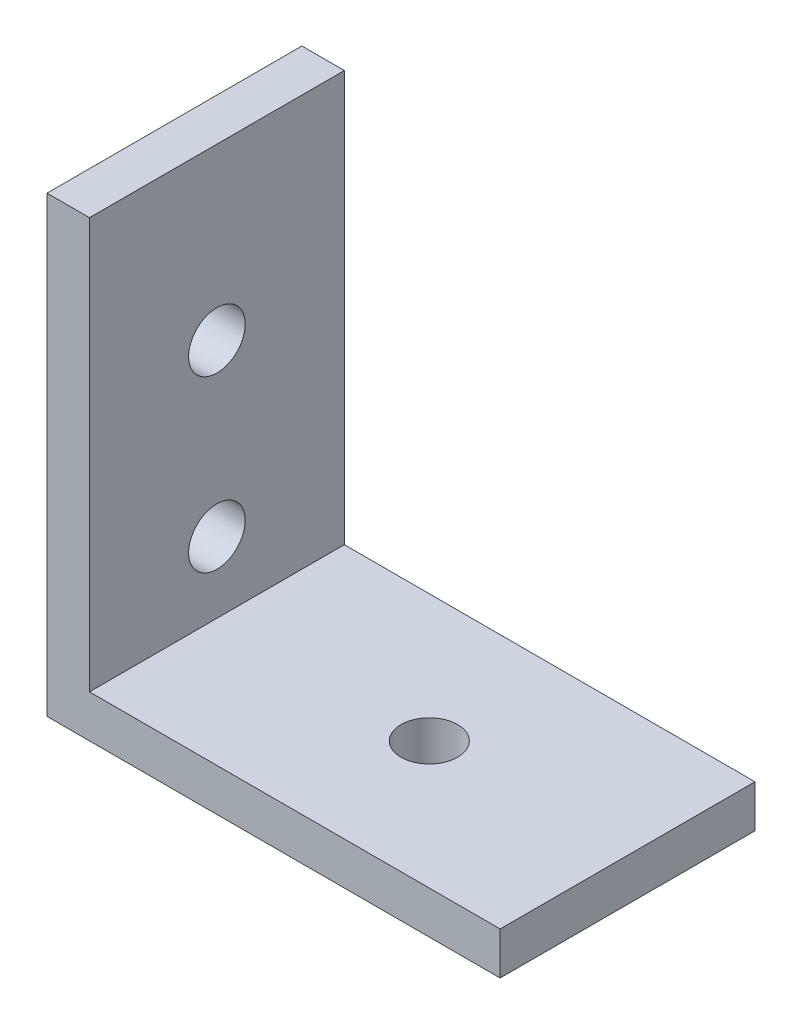
SolidWorks part; units mm, degrees
material "6063-O"
ref_plane "Front Plane" through (0, 0, 0) normal (0, 0, 1) x (1, 0, 0)
ref_plane "Top Plane" through (0, 0, 0) normal (0, 1, 0) x (1, 0, 0)
ref_plane "Right Plane" through (0, 0, 0) normal (1, 0, 0) x (0, 0, -1)
sketch "Sketch1" plane through (0, 0, 0) normal (0, 1, 0) x (1, 0, 0)
  line L1 (0, 0) -> (32, 0)
  line L2 (0, 0) -> (0, 18)
  line L3 (0, 18) -> (32, 18)
  line L4 (32, 0) -> (32, 18)
  dimension "D1" = 18
  dimension "D2" = 32
extrude "Boss-Extrude1" add sketch "Sketch1" along normal blind 3
sketch "Sketch2" plane through (0, 3, 0) normal (0, 1, 0) x (1, 0, 0)
  line L0 (32, 18) -> (0, 18) construction
  line L1 (0, 0) -> (3, 0)
  line L2 (0, 0) -> (0, 18)
  line L3 (0, 18) -> (3, 18)
  line L4 (3, 0) -> (3, 18)
  dimension "D1" = 3
extrude "Boss-Extrude2" add sketch "Sketch2" along normal blind 29
sketch "Sketch3" plane through (0, 3, 0) normal (0, 1, 0) x (1, 0, 0)
  line L1 (32, 0) -> (32, 18) construction
  line L2 (32, 18) -> (3, 18) construction
  circle A0 centre (18, 9) radius 2
  dimension "D1" = 14
  dimension "D3" = 4
  dimension "D2" = 9
extrude "Cut-Extrude1" cut sketch "Sketch3" against normal through all
sketch "Sketch4" plane through (3, 0, 0) normal (1, 0, 0) x (0, 0, -1)
  line L0 (0, 32) -> (0, 3) construction
  line L1 (0, 32) -> (18, 32) construction
  circle A0 centre (9, 20) radius 2
  circle A1 centre (9, 8) radius 2
  dimension "D1" = 9
  dimension "D3" = 4
  dimension "D2" = 24
  dimension "D4" = 12
extrude "Cut-Extrude2" cut sketch "Sketch4" against normal through all
